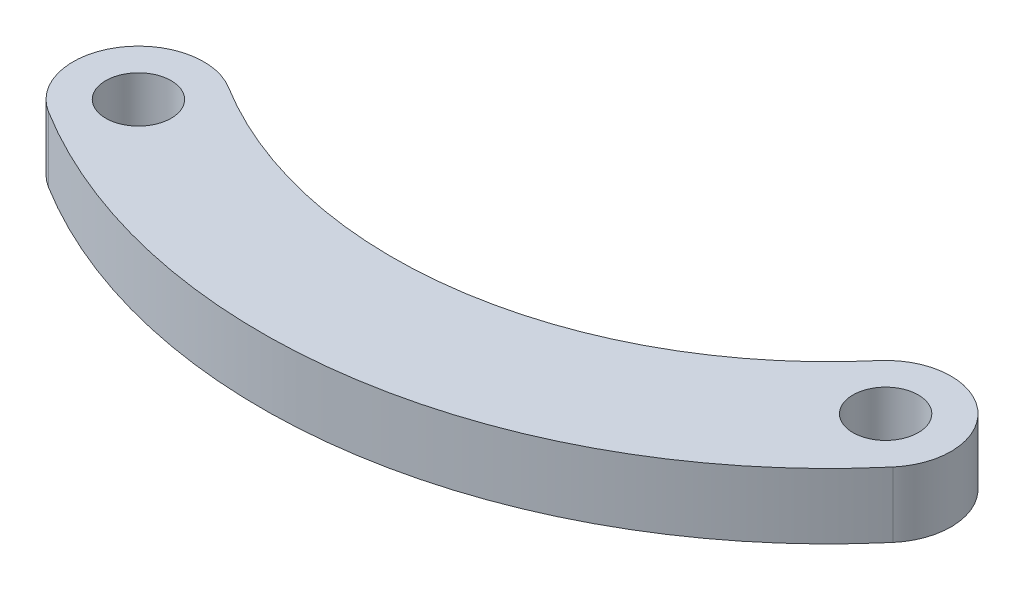
SolidWorks part; units mm, degrees
ref_plane "Front Plane" through (0, 0, 0) normal (0, 0, 1) x (1, 0, 0)
ref_plane "Top Plane" through (0, 0, 0) normal (0, 1, 0) x (1, 0, 0)
ref_plane "Right Plane" through (0, 0, 0) normal (1, 0, 0) x (0, 0, -1)
sketch "Sketch1" plane through (0, 0, 0) normal (0, 1, 0) x (1, 0, 0)
  arc A0 (-76.9291, -124.1472) -> (111.2666, -94.6063) centre (0, 0) ccw construction
  arc A1 (-86.9633, -140.3403) -> (125.7796, -106.9463) centre (0, 0) ccw
  arc A2 (-66.8948, -107.9541) -> (96.7535, -82.2664) centre (0, 0) ccw
  arc A3 (-66.8948, -107.9541) -> (-86.9633, -140.3403) centre (-76.9291, -124.1472) ccw
  arc A4 (125.7796, -106.9463) -> (96.7535, -82.2664) centre (111.2666, -94.6063) ccw
  circle A5 centre (-76.9291, -124.1472) radius 9.525
  circle A6 centre (111.2666, -94.6063) radius 9.525
  point P4 (22.648, -144.2833)
  dimension "D1" = 127
  dimension "D2" = 19.05
  dimension "D4" = 19.05
  dimension "D3" = 190.5
extrude "Boss-Extrude1" add sketch "Sketch1" along normal blind 19.05
